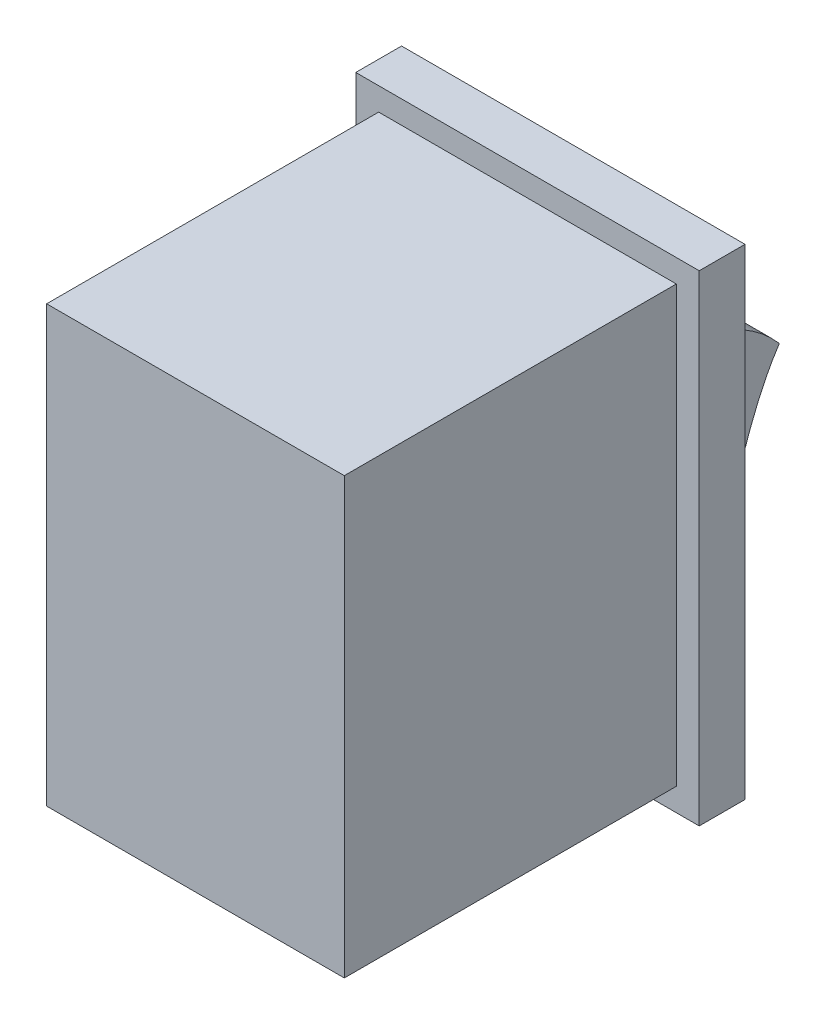
SolidWorks part; units mm, degrees
ref_plane "Front Plane" through (0, 0, 0) normal (0, 0, 1) x (1, 0, 0)
ref_plane "Top Plane" through (0, 0, 0) normal (0, 1, 0) x (1, 0, 0)
ref_plane "Right Plane" through (0, 0, 0) normal (1, 0, 0) x (0, 0, -1)
sketch "Sketch1" plane through (0, 0, 0) normal (0, 0, 1) x (1, 0, 0)
  line L1 (-6.5, -9.5) -> (6.5, -9.5)
  line L2 (-6.5, -9.5) -> (-6.5, 9.5)
  line L3 (-6.5, 9.5) -> (6.5, 9.5)
  line L4 (6.5, -9.5) -> (6.5, 9.5)
  line L5 (-6.5, -9.5) -> (6.5, 9.5) construction
  line L6 (-6.5, 9.5) -> (6.5, -9.5) construction
  point P0 (0, 0)
  dimension "D1" = 13
  dimension "D2" = 19
extrude "Boss-Extrude1" add sketch "Sketch1" along normal blind 14.5
sketch "Sketch2" plane through (0, 0, 0) normal (0, 0, 1) x (1, 0, 0)
  line L1 (-7.5, -10.5) -> (7.5, -10.5)
  line L2 (-7.5, -10.5) -> (-7.5, 10.5)
  line L3 (-7.5, 10.5) -> (7.5, 10.5)
  line L4 (7.5, -10.5) -> (7.5, 10.5)
  line L5 (-7.5, -10.5) -> (7.5, 10.5) construction
  line L6 (-7.5, 10.5) -> (7.5, -10.5) construction
  point P0 (0, 0)
  dimension "D1" = 21
  dimension "D2" = 15
extrude "Boss-Extrude2" add sketch "Sketch2" against normal blind 2
sketch "Sketch3" plane through (0, 0, 0) normal (1, 0, 0) x (0, 0, -1)
  line L0 (5.5, -15.8718) -> (5.5, 14.4281) construction
  line L1 (2, 10.5) -> (2, -10.5) construction
  line L2 (2, -7.5) -> (2, 6)
  line L3 (2, -10.5) -> (0, -10.5) construction
  line L4 (2, 10.5) -> (0, 10.5) construction
  spline S0 degree 2 poles (2, -7.5) (3.5367, 1.1278) (5.5, 4) knots 0 0 0 1 1 1
  spline S1 degree 2 poles (5.5, 4) (4.1147, 5.5982) (2, 6) knots 0 0 0 1 1 1
  point P10 (5.5, 4)
  dimension "D1" = 3.5
  dimension "D2" = 3
  dimension "D3" = 4.5
  dimension "D4" = 6.5
extrude "Boss-Extrude3" add sketch "Sketch3" along normal blind 5.5 and the other way blind 5.5
